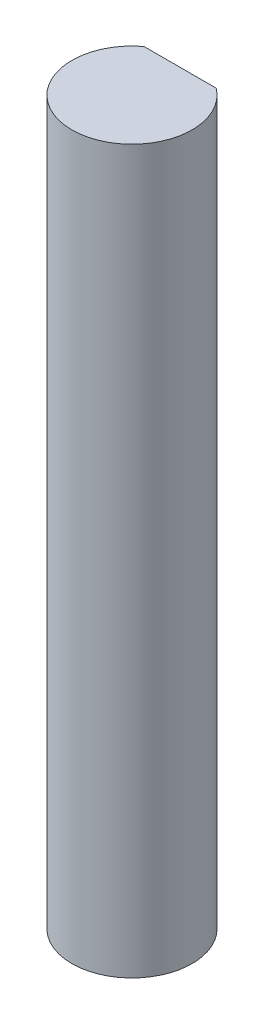
SolidWorks part; units mm, degrees
ref_plane "前视基准面" through (0, 0, 0) normal (0, 0, 1) x (1, 0, 0)
ref_plane "上视基准面" through (0, 0, 0) normal (0, 1, 0) x (1, 0, 0)
ref_plane "右视基准面" through (0, 0, 0) normal (1, 0, 0) x (0, 0, -1)
sketch "草图1" plane through (0, 0, 0) normal (0, 1, 0) x (1, 0, 0)
  line L0 (-1.5, 2) -> (1.5, 2)
  line L1 (0, 2) -> (0, -2.5) construction
  circle A0 centre (0, 0) radius 2.5
  dimension "D2" = 5
  dimension "D1" = 4.5
extrude "凸台-拉伸1" add sketch "草图1" along normal blind 30 contours L1 L0 A0 | L0 L1 A0
